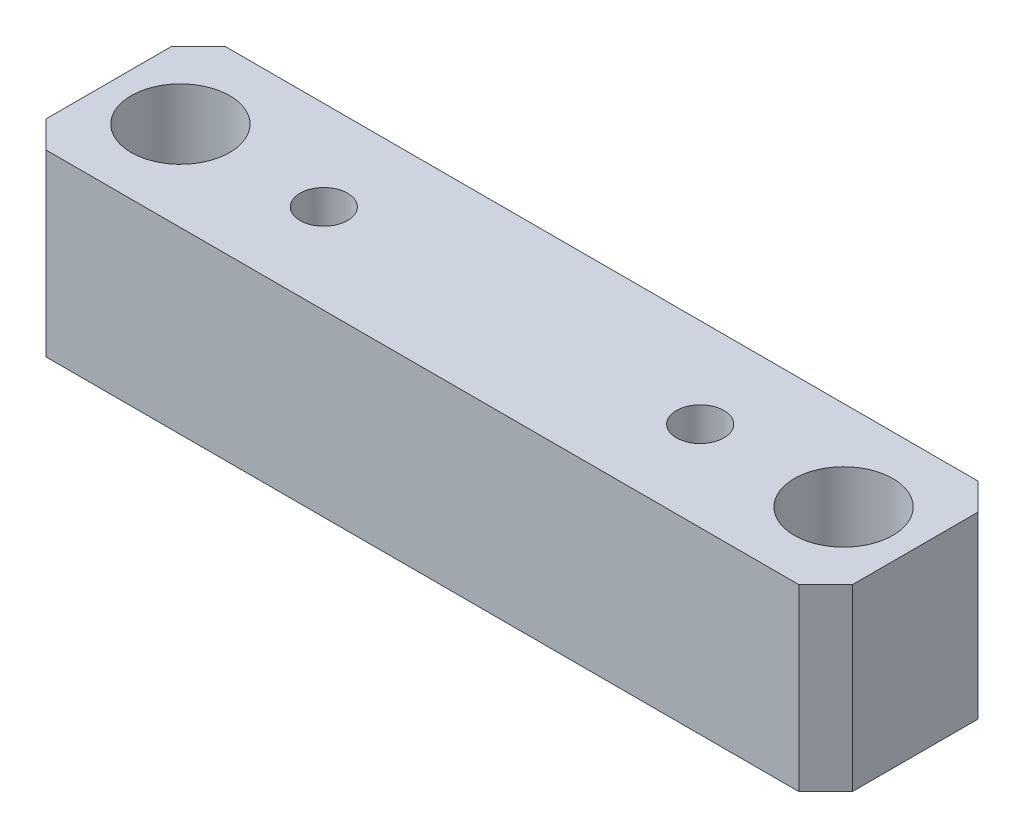
SolidWorks part; units mm, degrees
ref_plane "Front Plane" through (0, 0, 0) normal (0, 0, 1) x (1, 0, 0)
ref_plane "Top Plane" through (0, 0, 0) normal (0, 1, 0) x (1, 0, 0)
ref_plane "Right Plane" through (0, 0, 0) normal (1, 0, 0) x (0, 0, -1)
sketch "Sketch1" plane through (0, 0, 0) normal (0, 1, 0) x (1, 0, 0)
  line L0 (-21, 0) -> (21, 0) construction
  line L1 (-45, -10) -> (45, -10)
  line L2 (-45, -10) -> (-45, 10)
  line L3 (-45, 10) -> (45, 10)
  line L4 (45, -10) -> (45, 10)
  line L5 (-45, -10) -> (45, 10) construction
  line L6 (-45, 10) -> (45, -10) construction
  line L7 (-45, 0) -> (-37, 0) construction
  line L8 (45, 0) -> (37, 0) construction
  circle A0 centre (-21, 0) radius 2.65
  circle A1 centre (21, 0) radius 2.65
  circle A2 centre (-37, 0) radius 2.75
  circle A3 centre (37, 0) radius 2.75
  point P0 (0, 0)
  point P9 (0, 0)
  dimension "D4" = 8
  dimension "D1" = 42
  dimension "D2" = 90
  dimension "D3" = 20
  dimension "D5" = 8
extrude "Boss-Extrude1" add sketch "Sketch1" along normal blind 20
sketch "Sketch2" plane through (0, 0, 0) normal (0, -1, 0) x (1, 0, 0)
  line L1 (-16.2657, 0) -> (-18.6329, 4.1)
  line L2 (-18.6329, 4.1) -> (-23.3671, 4.1)
  line L3 (-23.3671, 4.1) -> (-25.7343, 0)
  line L4 (-25.7343, 0) -> (-23.3671, -4.1)
  line L5 (-23.3671, -4.1) -> (-18.6329, -4.1)
  line L6 (-18.6329, -4.1) -> (-16.2657, 0)
  line L7 (25.7343, 0) -> (23.3671, 4.1)
  line L8 (23.3671, 4.1) -> (18.6329, 4.1)
  line L9 (18.6329, 4.1) -> (16.2657, 0)
  line L10 (16.2657, 0) -> (18.6329, -4.1)
  line L11 (18.6329, -4.1) -> (23.3671, -4.1)
  line L12 (23.3671, -4.1) -> (25.7343, 0)
  circle A0 centre (-21, 0) radius 4.1 construction
  circle A1 centre (21, 0) radius 4.1 construction
  dimension "D1" = 8.2
  dimension "D2" = 8.2
extrude "Cut-Extrude1" cut sketch "Sketch2" against normal blind 12
sketch "Sketch3" plane through (0, 20, 0) normal (0, 1, 0) x (1, 0, 0)
  circle A0 centre (-37, 0) radius 5.5
  circle A1 centre (37, 0) radius 5.5
  dimension "D1" = 11
  dimension "D2" = 11
extrude "Cut-Extrude2" cut sketch "Sketch3" against normal blind 14
chamfer "Chamfer1" distance 3 angle 45 4 edges at (45, 10, 10) (-45, 10, 10) (45, 10, -10) (-45, 10, -10)
